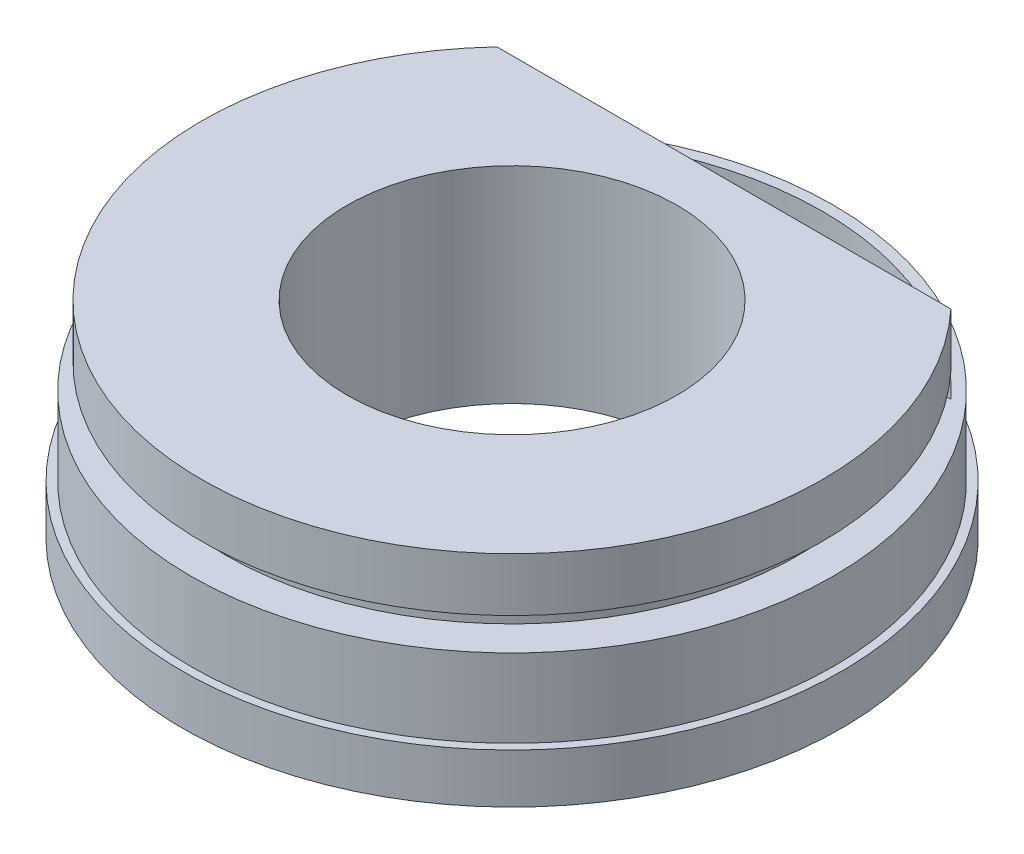
SolidWorks part; units mm, degrees
ref_plane "Front Plane" through (0, 0, 0) normal (0, 0, 1) x (1, 0, 0)
ref_plane "Top Plane" through (0, 0, 0) normal (0, 1, 0) x (1, 0, 0)
ref_plane "Right Plane" through (0, 0, 0) normal (1, 0, 0) x (0, 0, -1)
sketch "Sketch1" plane through (0, 0, 0) normal (0, 0, 1) x (1, 0, 0)
  line L0 (10, 0) -> (20, 0)
  line L1 (20, 0) -> (20, 3)
  line L2 (20, 3) -> (19.5, 3)
  line L3 (19.5, 3) -> (19.5, 7.75)
  line L4 (19.5, 7.75) -> (17.3434, 7.75)
  line L5 (17.3434, 7.75) -> (17.3434, 9.25)
  line L6 (17.3434, 9.25) -> (18.8434, 9.25)
  line L7 (18.8434, 9.25) -> (18.8434, 12.5)
  line L8 (18.8434, 12.5) -> (10, 12.5)
  line L9 (10, 12.5) -> (10, 0)
  line L10 (0, 0) -> (0, 14.2024) construction
  dimension "D2" = 3
  dimension "D3" = 0.5
  dimension "D4" = 4.75
  dimension "D5" = 1.5
  dimension "1.5" = 1.5
  dimension "D6" = 12.5
revolve "Revolve2" add sketch "Sketch1" angle 360 about L10
sketch "Sketch2" plane through (0, 12.5, 0) normal (0, 1, 0) x (1, 0, 0)
  line L0 (-14.6614, 12.8566) -> (14.6614, 12.8566)
  line L1 (0, -18.8434) -> (5.0176, -18.8434)
  circle A0 centre (0, 0) radius 19.5 construction
  circle A1 centre (0, 0) radius 19.5 construction
  circle A2 centre (0, 0) radius 18.8434 construction
  arc A3 (14.6614, 12.8566) -> (5.0176, -18.8434) centre (0, 0) ccw
  circle M6 centre (0, 0) radius 18.8434
  dimension "D1" = 31.7
extrude "Cut-Extrude3" cut sketch "Sketch2" against normal blind 10 contours L0 M6
